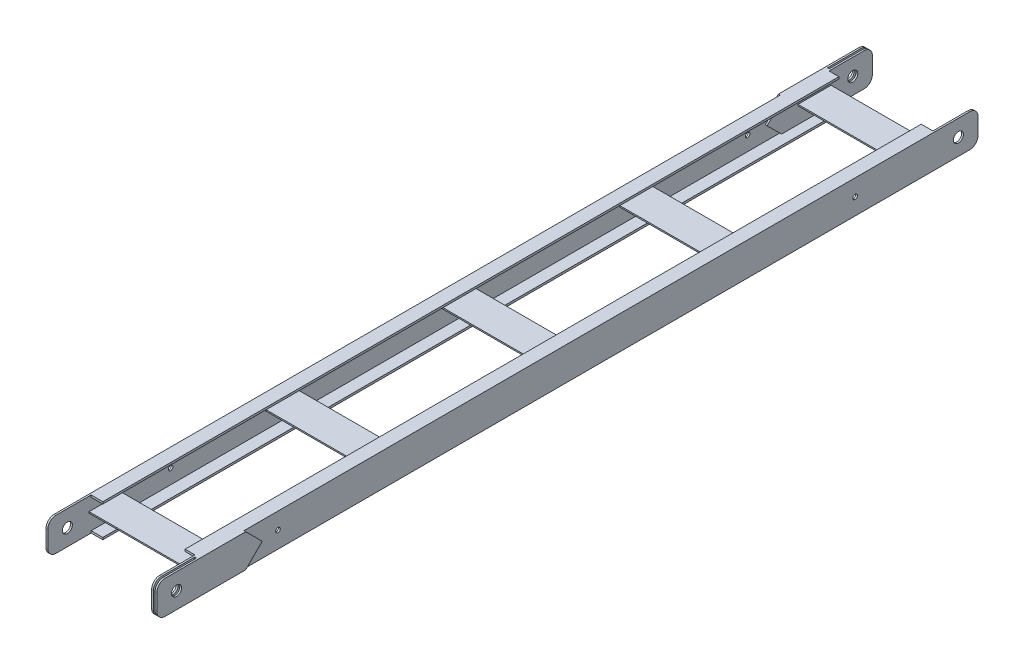
SolidWorks part; units mm, degrees
ref_plane "前视基准面" through (0, 0, 0) normal (0, 0, 1) x (1, 0, 0)
ref_plane "上视基准面" through (0, 0, 0) normal (0, 1, 0) x (1, 0, 0)
ref_plane "右视基准面" through (0, 0, 0) normal (1, 0, 0) x (0, 0, -1)
sketch "草图2" plane through (0, 0, 0) normal (0, 0, 1) x (1, 0, 0)
  line L0 (0, 0) -> (0, 160)
  line L1 (0, 160) -> (65, 160)
  line L2 (65, 160) -> (65, 150)
  line L3 (65, 150) -> (8.5, 150)
  line L4 (8.5, 150) -> (8.5, 10)
  line L5 (8.5, 10) -> (65, 10)
  line L6 (65, 10) -> (65, 0)
  line L7 (65, 0) -> (0, 0)
  line L8 (463.5, 160) -> (528.5, 160)
  line L9 (528.5, 160) -> (528.5, 0)
  line L10 (528.5, 0) -> (463.5, 0)
  line L11 (463.5, 0) -> (463.5, 10)
  line L12 (463.5, 10) -> (520, 10)
  line L13 (520, 10) -> (520, 150)
  line L14 (520, 150) -> (463.5, 150)
  line L15 (463.5, 150) -> (463.5, 160)
  dimension "D1" = 160
  dimension "D2" = 10
  dimension "D3" = 8.5
  dimension "D4" = 65
  dimension "D5" = 528.5
extrude "拉伸1" add sketch "草图2" along normal blind 3985
sketch "草图5" plane through (0, 0, 0) normal (-1, 0, 0) x (0, 0, 1)
  line L0 (200, 95) -> (360, 95)
  line L1 (360, 95) -> (360, 88.5)
  line L2 (283.25, 88.5) -> (360, 88.5)
  line L3 (283.25, 88.5) -> (283.25, 48.5)
  line L4 (283.25, 48.5) -> (276.75, 48.5)
  line L5 (276.75, 48.5) -> (276.75, 88.5)
  line L6 (276.75, 88.5) -> (200, 88.5)
  line L7 (200, 88.5) -> (200, 95)
  line L8 (0, 160) -> (0, 0) construction
  point P10 (0, 80)
  dimension "D1" = 160
  dimension "D2" = 6.5
  dimension "D3" = 6.5
  dimension "D4" = 40
  dimension "D5" = 200
  dimension "D6" = 15
extrude "拉伸3" add sketch "草图5" against normal blind 520
sketch "草图6" plane through (0, 160, 0) normal (0, 1, 0) x (1, 0, 0)
  line L0 (528.5, 0) -> (463.5, 0) construction
  line L1 (520, 0) -> (8.5, 0)
  line L2 (520, 0) -> (520, -200)
  line L3 (520, -200) -> (8.5, -200)
  line L4 (8.5, 0) -> (8.5, -200)
  line L5 (65, -3985) -> (0, -3985) construction
  line L6 (520, -3785) -> (8.5, -3785)
  line L7 (520, -3785) -> (520, -3985)
  line L8 (520, -3985) -> (8.5, -3985)
  line L9 (8.5, -3785) -> (8.5, -3985)
  line L10 (528.5, -3985) -> (528.5, 0) construction
  line L11 (0, -3985) -> (0, 0) construction
  dimension "D1" = 8.5
  dimension "D2" = 8.5
  dimension "D3" = 200
  dimension "D4" = 200
  dimension "D5" = 8.5
  dimension "D6" = 8.5
extrude "拉伸4" cut sketch "草图6" against normal through all
pattern_linear "阵列(线性)1" count 5 spacing 856.25 along (0, 0, 1) of "拉伸3"
sketch "草图19" plane through (528.5, 0, 0) normal (1, 0, 0) x (0, 0, -1)
  line L0 (-3985, 0) -> (0, 0) construction
  line L1 (-3985, 160) -> (-3555, 160)
  line L2 (-3985, 160) -> (-3985, 0)
  line L3 (-3985, 0) -> (-3555, 0)
  line L4 (-3555, 160) -> (-3475, 80)
  line L5 (-3475, 80) -> (-3555, 0)
  dimension "D1" = 430
extrude "拉伸11" add sketch "草图19" along normal blind 8.5
pattern_linear "阵列(线性)2" count 2 spacing 17 along (-1, 0, 0) of "拉伸11"
sketch "草图22" plane through (0, 160, 0) normal (0, 1, 0) x (1, 0, 0)
  line L0 (537, -3985) -> (511.5, -3985) construction
  line L1 (520, -3785) -> (528.5, -3785)
  line L2 (520, -3785) -> (520, -3985)
  line L3 (520, -3985) -> (528.5, -3985)
  line L4 (528.5, -3785) -> (528.5, -3985)
  line L5 (537, -3555) -> (537, -3985) construction
  line L6 (511.5, -3785) -> (511.5, -3985) construction
  line L7 (511.5, -3785) -> (463.5, -3785) construction
  dimension "D1" = 8.5
  dimension "D2" = 8.5
extrude "拉伸12" cut sketch "草图22" against normal through all
sketch "草图23" plane through (0, 0, 0) normal (-1, 0, 0) x (0, 0, 1)
  line L0 (0, 160) -> (0, 0) construction
  line L2 (3985, 0) -> (0, 0) construction
  line L3 (3985, 160) -> (3985, 0) construction
  line L4 (3985, 160) -> (0, 160) construction
  circle A0 centre (95, 80) radius 24.25
  circle A1 centre (3890, 80) radius 24.25
  dimension "D3" = 48.5
  dimension "D4" = 48.5
  dimension "D1" = 95
  dimension "D2" = 80
  dimension "D5" = 95
  dimension "D6" = 80
extrude "拉伸13" cut sketch "草图23" against normal through all
sketch "草图26" plane through (0, 0, 0) normal (-1, 0, 0) x (0, 0, 1)
  line L0 (0, 160) -> (0, 0)
  line L1 (0, 160) -> (430, 160)
  line L2 (430, 160) -> (510, 80)
  line L3 (510, 80) -> (430, 0)
  line L4 (0, 0) -> (430, 0)
  dimension "D1" = 430
extrude "拉伸14" add sketch "草图26" along normal blind 8.5
pattern_linear "阵列(线性)3" count 2 spacing 17 along (1, 0, 0) of "拉伸14"
sketch "草图27" plane through (0, 160, 0) normal (0, 1, 0) x (1, 0, 0)
  line L0 (17, 0) -> (-8.5, 0) construction
  line L1 (0, 0) -> (8.5, 0)
  line L2 (0, 0) -> (0, -200)
  line L3 (0, -200) -> (8.5, -200)
  line L4 (8.5, 0) -> (8.5, -200)
  line L5 (-8.5, -430) -> (-8.5, 0) construction
  line L6 (17, -200) -> (17, 0) construction
  line L7 (17, -200) -> (65, -200) construction
  dimension "D1" = 8.5
  dimension "D2" = 8.5
extrude "拉伸15" cut sketch "草图27" against normal through all
sketch "草图28" plane through (-8.5, 0, 0) normal (-1, 0, 0) x (0, 0, 1)
  line L0 (0, 160) -> (0, 0) construction
  line L1 (430, 160) -> (0, 160) construction
  circle A0 centre (95, 80) radius 24.25
  dimension "D1" = 48.5
  dimension "D2" = 95
  dimension "D3" = 80
extrude "拉伸16" cut sketch "草图28" against normal through all
fillet "圆角2" radius 40 10 edges at (4.25, 160, 3985) (4.25, 0, 3985) (532.75, 0, 3985) (532.75, 160, 3985) (-4.25, 160, 0) (12.75, 160, 0) (-4.25, 0, 0) (12.75, 0, 0) (524.25, 160, 0) (524.25, 0, 0)
sketch "草图29" plane through (0, 0, 3785) normal (0, 0, 1) x (1, 0, 0)
  line L1 (8.5, 160) -> (511.5, 160)
  line L2 (8.5, 160) -> (8.5, 150)
  line L3 (8.5, 150) -> (511.5, 150)
  line L4 (511.5, 160) -> (511.5, 150)
  line L5 (511.5, 0) -> (8.5, 0)
  line L6 (511.5, 0) -> (511.5, 10)
  line L7 (511.5, 10) -> (8.5, 10)
  line L8 (8.5, 0) -> (8.5, 10)
extrude "拉伸17" cut sketch "草图29" against normal blind 10
sketch "草图30" plane through (0, 0, 200) normal (0, 0, -1) x (-1, 0, 0)
  line L1 (-17, 160) -> (-520, 160)
  line L2 (-17, 160) -> (-17, 150)
  line L3 (-17, 150) -> (-520, 150)
  line L4 (-520, 160) -> (-520, 150)
  line L5 (-520, 10) -> (-17, 10)
  line L6 (-520, 10) -> (-520, 0)
  line L7 (-520, 0) -> (-17, 0)
  line L8 (-17, 10) -> (-17, 0)
extrude "拉伸18" cut sketch "草图30" against normal blind 10
sketch "草图31" plane through (528.5, 0, 0) normal (1, 0, 0) x (0, 0, -1)
  line L0 (-95, 80) -> (-3890, 80) construction
  circle A0 centre (-595, 80) radius 11
  circle A1 centre (-3390, 80) radius 11
  dimension "D1" = 22
  dimension "D2" = 22
  dimension "D3" = 500
  dimension "D4" = 500
extrude "拉伸19" cut sketch "草图31" against normal through all
